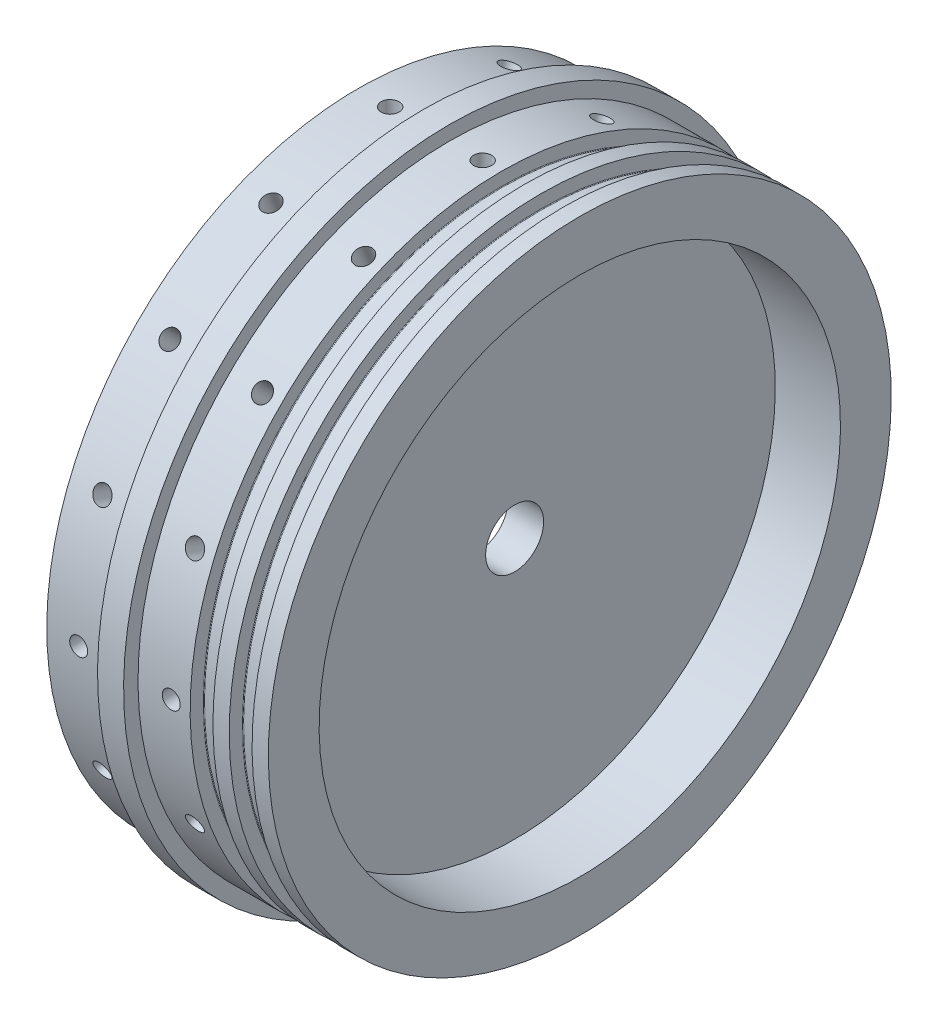
SolidWorks part; units mm, degrees
material "6061 Alloy"
ref_plane "Front Plane" through (0, 0, 0) normal (0, 0, 1) x (1, 0, 0)
ref_plane "Top Plane" through (0, 0, 0) normal (0, 1, 0) x (1, 0, 0)
ref_plane "Right Plane" through (0, 0, 0) normal (1, 0, 0) x (0, 0, -1)
sketch "Sketch4" plane through (0, 0, 0) normal (0, 0, 1) x (1, 0, 0)
  line L0 (0, 0) -> (0, 63.5)
  line L1 (0, 63.5) -> (5.08, 63.5)
  line L2 (5.08, 63.5) -> (5.08, 60.6933)
  line L3 (5.08, 60.6933) -> (15.24, 60.6933)
  line L4 (15.24, 60.6933) -> (15.24, 58.1406)
  line L5 (15.367, 58.0136) -> (19.558, 58.0136)
  line L6 (19.685, 58.1406) -> (19.685, 60.6933)
  line L7 (19.685, 60.6933) -> (22.86, 60.6933)
  line L8 (22.86, 60.6933) -> (22.86, 58.1406)
  line L9 (22.987, 58.0136) -> (27.178, 58.0136)
  line L10 (27.305, 58.1406) -> (27.305, 60.6933)
  line L11 (27.305, 60.6933) -> (30.48, 60.6933)
  line L12 (30.48, 60.6933) -> (30.48, 0)
  line L13 (30.48, 0) -> (0, 0)
  line L14 (15.24, 60.6933) -> (19.685, 60.6933) construction
  line L15 (22.86, 60.6933) -> (27.305, 60.6933) construction
  arc A0 (15.24, 58.1406) -> (15.367, 58.0136) centre (15.367, 58.1406) ccw
  arc A1 (19.685, 58.1406) -> (19.558, 58.0136) centre (19.558, 58.1406) cw
  arc A2 (22.86, 58.1406) -> (22.987, 58.0136) centre (22.987, 58.1406) ccw
  arc A3 (27.305, 58.1406) -> (27.178, 58.0136) centre (27.178, 58.1406) cw
  point P17 (15.24, 58.0136)
  point P21 (19.685, 58.0136)
  dimension "D9" = 0.127
  dimension "D2" = 5.08
  dimension "D5" = 10.16
  dimension "D7" = 4.445
  dimension "D4" = 3.175
  dimension "D6" = 63.5
  dimension "D3" = 3.175
  dimension "D1" = 2.5527
  dimension "D8" = 2.8067
revolve "Revolve1" add sketch "Sketch4" angle 360 about L13
sketch3d "3DSketch3"
  circle A0 centre (11.24, 0, 60.6933) radius 1.5
  circle A1 centre (15.24, 0, 0) radius 60.6933 construction
  point P2 (11.24, 0, 62.1933)
  point P5 (75.9333, 0, 0)
  point P6 (15.24, 0, 60.6933)
  point P7 (15.24, 0, 60.6933)
  dimension "D1" = 3
  dimension "D2" = 4
hole_wizard "#6-32 Tapped Hole1" positions "3DSketch4" profile "Sketch5" tap size "#6-32" standard "ANSI Inch"
sketch3d "3DSketch4"
  line L0 (11.557, 0, 60.6933) -> (15.24, 0, 60.6933) construction
  line L2 (11.557, 0, 60.6933) -> (5.08, 0, 60.6933) construction
  circle A1 centre (15.24, 0, 0) radius 60.6933 construction
  circle A2 centre (5.08, 0, 0) radius 60.6933 construction
  circle A3 centre (11.557, 0, 60.6933) radius 1.905 construction
  point P10 (11.557, 0, 60.6933)
  point P18 (75.9333, 0, 0)
  point P24 (65.7733, 0, 0)
  point P27 (11.557, 0, 62.5983)
  dimension "D1" = 3.81
  dimension "D2" = 6.477
sketch "Sketch5" plane through (11.557, 0, 60.6933) normal (1, 0, 0) x (0, -1, 0)
  line L0 (0, 0) -> (0, 10.9727)
  line L1 (0, 10.9727) -> (1.3525, 10.16)
  line L2 (1.3525, 10.16) -> (1.3525, 7.62)
  line L3 (1.3525, 7.62) -> (1.7526, 7.62)
  line L4 (1.7526, 7.62) -> (1.7526, 0)
  line L5 (1.7526, 0) -> (0, 0)
  line L10 (0, 10.9727) -> (-1.3526, 10.16) construction
  line L11 (0, -6.35) -> (0, 107.95) construction
  dimension "Tap Drill Dia." = 2.7051
  dimension "Tap Drill Depth" = 10.16
  dimension "Thread Major Dia." = 3.5052
  dimension "Thread Depth" = 7.62
  dimension "Drill Angle" = 118
sketch "Sketch6" plane through (0, 0, 0) normal (-1, 0, 0) x (0, 0, 1)
  circle A0 centre (0, 0) radius 60.6933
  circle A1 centre (0, 0) radius 63.5 construction
  dimension "D1" = 2.8067
extrude "Boss-Extrude1" add sketch "Sketch6" along normal blind 12.7
ref_plane "Plane2" through (2.54, 0, 0) normal (1, 0, 0) x (0, 0, -1)
sketch "Sketch8" plane through (30.48, 0, 0) normal (1, 0, 0) x (0, 0, -1)
  circle A0 centre (0, 0) radius 50.8
  circle A1 centre (0, 0) radius 60.6933 construction
  dimension "D1" = 9.8933
extrude "Cut-Extrude1" cut sketch "Sketch8" against normal blind 12.7
sketch "Sketch9" plane through (-12.7, 0, 0) normal (-1, 0, 0) x (0, 0, 1)
  circle A0 centre (0, 0) radius 50.8
  circle A1 centre (0, 0) radius 60.6933 construction
  dimension "D1" = 9.8933
extrude "Cut-Extrude2" cut sketch "Sketch9" against normal blind 3.175
sketch "Sketch10" plane through (-9.525, 0, 0) normal (-1, 0, 0) x (0, 0, 1)
  circle A1 centre (0, 0) radius 42.35
  circle A2 centre (0, 0) radius 50.8 construction
  dimension "D1" = 8.45
extrude "Cut-Extrude3" cut sketch "Sketch10" against normal blind 20.32
sketch "Sketch11" plane through (17.78, 0, 0) normal (1, 0, 0) x (0, 0, -1)
  circle A0 centre (0, 0) radius 9.5
ref_plane "Plane3" through (2.54, 0, 0) normal (-1, 0, 0) x (0, 0, 1)
pattern_circular "CirPattern1" count 16 over 360 about axis through (0, 0, 0) along (1, 0, 0) of "#6-32 Tapped Hole1"
mirror "Mirror1" about plane through (2.54, 0, 0) normal (-1, 0, 0) of "CirPattern1", "#6-32 Tapped Hole1"
hole_wizard "Ø11.2 (11.3) Diameter Hole1" positions "3DSketch5" profile "Sketch12" hole size "Ø11.2" standard "ANSI Metric" end condition through all
sketch3d "3DSketch5"
  point P0 (17.78, 0, 0)
sketch "Sketch12" plane through (17.78, 0, 0) normal (0, 1, 0) x (0, 0, -1)
  line L0 (0, 0) -> (0, 30.48)
  line L1 (0, 30.48) -> (5.65, 30.48)
  line L2 (5.65, 30.48) -> (5.65, 0)
  line L5 (5.65, 0) -> (0, 0)
  line L11 (0, -6.35) -> (0, 107.95) construction
  dimension "Thru Hole Dia." = 11.3
  dimension "Thru Hole Depth" = 30.48
equation "\"D9@Sketch4\"=.005in"
